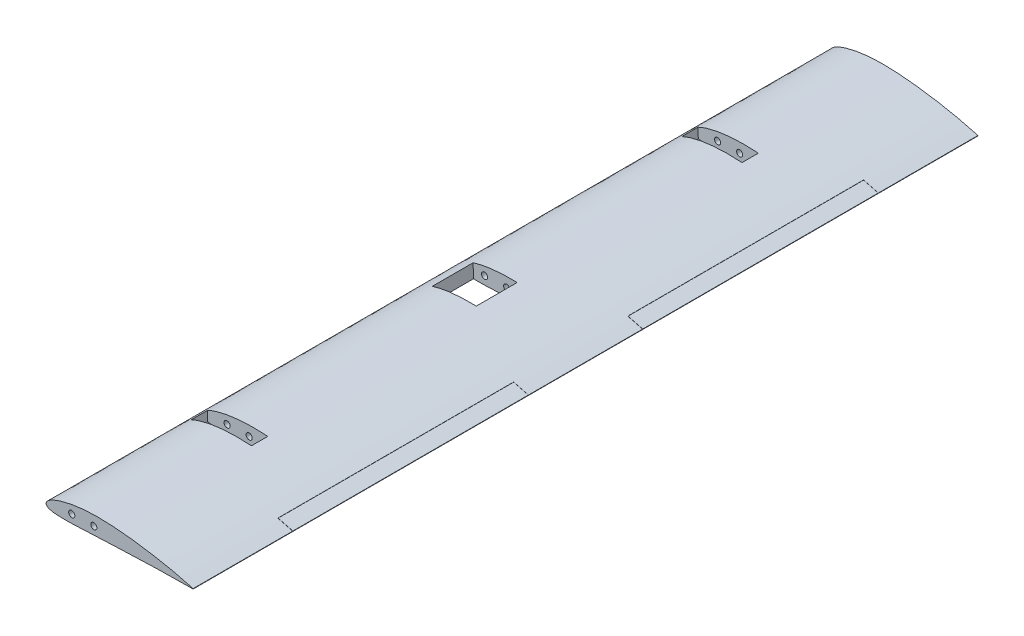
SolidWorks part; units mm, degrees
ref_plane "Front Plane" through (0, 0, 0) normal (0, 0, 1) x (1, 0, 0)
ref_plane "Top Plane" through (0, 0, 0) normal (0, 1, 0) x (1, 0, 0)
ref_plane "Right Plane" through (0, 0, 0) normal (1, 0, 0) x (0, 0, -1)
curve "NACA 4412"
  spline degree 3 poles (25.4, 0.033, 0) (24.9771, 0.1481, 0) (24.1334, 0.3778, 0) (22.4431, 0.7955, 0) (20.3293, 1.2569, 0) (17.7869, 1.7118, 0) (15.2464, 2.0846, 0) (12.7045, 2.3505, 0) (10.1628, 2.5164, 0) (8.041, 2.5181, 0) (6.3469, 2.4009, 0) (5.0745, 2.2465, 0) (3.7995, 2.0188, 0) (2.7428, 1.745, 0) (1.8961, 1.4685, 0) (1.2577, 1.2074, 0) (0.7129, 0.9251, 0) (0.2401, 0.5874, 0) (-0.1715, 0.0442, 0) (0.2727, -0.3711, 0) (0.7261, -0.5342, 0) (1.266, -0.6443, 0) (1.9036, -0.7002, 0) (2.7513, -0.7398, 0) (3.8103, -0.7368, 0) (5.0806, -0.7013, 0) (6.3499, -0.6336, 0) (8.0433, -0.5544, 0) (10.1596, -0.4528, 0) (12.7001, -0.3574, 0) (15.2397, -0.2514, 0) (17.7796, -0.1611, 0) (20.3198, -0.0947, 0) (22.4366, -0.061, 0) (24.13, -0.0388, 0) (24.9767, -0.035, 0) (25.4, -0.033, 0) knots 0 0 0 0 0.025305 0.050488 0.10052 0.150191 0.199587 0.24874 0.297716 0.346601 0.371103 0.395726 0.42057 0.445825 0.458702 0.47192 0.485786 0.493461 0.506863 0.516148 0.522766 0.535269 0.547551 0.559786 0.584229 0.608681 0.633151 0.657622 0.706558 0.755482 0.804406 0.85332 0.902221 0.951113 0.975557 1 1 1 1
sketch "Sketch2" plane through (0, 0, 0) normal (0, 0, 1) x (1, 0, 0)
  line L1 (228.6, 12.387) -> (228.6, 11.7928)
  line L2 (40.005, 31.2493) -> (40.005, 5.6305) construction
  line L4 (74.2832, 19.3375) -> (40.005, 18.4399) construction
  line L5 (0, 0) -> (0, 12.7) construction
  line L6 (40.005, 18.4399) -> (60.8151, 18.4399) construction
  circle A0 centre (40.005, 18.4399) radius 4.7625
  circle A1 centre (74.2832, 19.3375) radius 4.7625
  spline S1 degree 3 poles (228.6, 12.387) (224.795, 13.4228) (217.2034, 15.4895) (201.9951, 19.2471) (182.9766, 23.3988) (160.101, 27.4914) (137.2432, 30.846) (114.3726, 33.2389) (91.504, 34.7313) (72.413, 34.7464) (57.1699, 33.6918) (45.7222, 32.3028) (34.2497, 30.2543) (24.7428, 27.7908) (17.1245, 25.3027) (11.3801, 22.9538) (6.4787, 20.4136) (2.2242, 17.375) (-1.4793, 12.488) (2.5182, 8.7506) (6.5972, 7.2835) (11.455, 6.2932) (17.1921, 5.7898) (24.819, 5.4335) (34.3469, 5.4602) (45.7763, 5.78) (57.1976, 6.389) (72.4334, 7.1015) (91.4748, 8.016) (114.3327, 8.8746) (137.1833, 9.8281) (160.036, 10.6401) (182.8906, 11.2375) (201.9369, 11.5408) (217.1729, 11.7405) (224.791, 11.7754) (228.6, 11.7928) knots 0 0 0 0 0.025305 0.050488 0.10052 0.150191 0.199587 0.24874 0.297716 0.346601 0.371103 0.395726 0.42057 0.445825 0.458702 0.47192 0.485786 0.493461 0.506863 0.516148 0.522766 0.535269 0.547551 0.559786 0.584229 0.608681 0.633151 0.657622 0.706558 0.755482 0.804406 0.85332 0.902221 0.951113 0.975557 1 1 1 1
  point P11 (40.005, 18.4399)
  dimension "D3" = 9.525
  dimension "D4" = 9.525
  dimension "D1" = 228.6
  dimension "D5" = 34.29
  dimension "D6" = 12.7
  dimension "D8" = 1.5
  dimension "D9" = 40.005
extrude "Extrude airfoil" add sketch "Sketch2" along normal blind 1219.2
sketch "Sketch3" plane through (0, 0, 0) normal (0, 1, 0) x (1, 0, 0)
  line L1 (228.6, -520.7) -> (205.74, -520.7)
  line L4 (205.74, -520.7) -> (205.74, -154.94)
  line L5 (228.6, -154.94) -> (205.74, -154.94)
  line L8 (0, 0) -> (0, -1219.2) construction
  line L9 (0, -609.6) -> (228.6, -609.6) construction
  line L10 (228.6, -1064.26) -> (228.6, -698.5)
  line L15 (228.6, -154.94) -> (228.6, -520.7)
  line L17 (228.6, -1219.2) -> (228.6, 0) construction
  line L18 (228.6, -1064.26) -> (205.74, -1064.26)
  line L19 (205.74, -698.5) -> (205.74, -1064.26)
  line L20 (228.6, -698.5) -> (205.74, -698.5)
  dimension "D1" = 22.86
  dimension "D2" = 365.76
  dimension "D3" = 88.9
extrude "Ailerons" cut sketch "Sketch3" against normal through all and the other way through all thin
ref_plane "Plane1" through (-0.4551, 17.3804, 0) normal (-0.0262, 0.9997, 0) x (0, 0, -1)
sketch "Sketch5" plane through (-0.4551, 17.3804, 0) normal (-0.0262, 0.9997, 0) x (0, 0, -1)
  line L0 (0, 0) -> (-1219.2, 0)
  line L1 (-609.6, 0) -> (-609.6, -227.3868) construction
  line L2 (-609.6, -57.15) -> (-990.6, -57.15) construction
  line L3 (-215.9, -10.16) -> (-241.3, -104.14) construction
  line L4 (-1003.3, -104.14) -> (-977.9, -104.14)
  line L5 (-1003.3, -104.14) -> (-1003.3, -10.16)
  line L6 (-1003.3, -10.16) -> (-977.9, -10.16)
  line L7 (-977.9, -104.14) -> (-977.9, -10.16)
  line L8 (-1003.3, -104.14) -> (-977.9, -10.16) construction
  line L9 (-1003.3, -10.16) -> (-977.9, -104.14) construction
  line L10 (-215.9, -104.14) -> (-241.3, -10.16) construction
  line L11 (-241.3, -104.14) -> (-241.3, -10.16)
  line L12 (-215.9, -104.14) -> (-215.9, -10.16)
  line L13 (-215.9, -104.14) -> (-241.3, -104.14)
  line L14 (-215.9, -10.16) -> (-241.3, -10.16)
  line L16 (-577.85, -91.44) -> (-641.35, -91.44)
  line L17 (-577.85, -91.44) -> (-577.85, -22.86)
  line L18 (-577.85, -22.86) -> (-641.35, -22.86)
  line L19 (-641.35, -91.44) -> (-641.35, -22.86)
  point P19 (-609.6, -22.86)
  dimension "D1" = 1219.2
  dimension "D2" = 57.15
  dimension "D3" = 25.4
  dimension "D4" = 93.98
  dimension "D5" = 381
  dimension "D6" = 22.86
  dimension "D7" = 91.44
  dimension "D8" = 31.75
extrude "Cut-Extrude1" cut sketch "Sketch5" against normal through all and the other way through all contours L12 L14 L11 L13 | L7 L6 L5 L4 | L18 L19 L16 L17
equation "\"span\"= 48"
equation "\"D1@Extrude airfoil\"=\"span\""
equation "\"wing_chord\"= 9"
equation "\"D1@Sketch2\"= \"wing_chord\""
equation "\"D1@Sketch3\"=\"wing_chord\"*0.1"
equation "\"D2@Sketch3\"=\"span\"/2*0.6"
equation "\"fuse_len\"= 15"
equation "\"fuse_height\"= 5"
equation "\"fuse_wid\"= 5"
equation "\"foam_t\"= 0.1875"
equation "\"main_spar_len\"= 36"
equation "\"x_fuse_to_wing\"= 3"
equation "\"x_cg_from_le\"= 2.25"
equation "\"boom_len\"= 30"
equation "\"wing_spar_d\"= 0.375"
equation "\"wing_spar_spacing\"= 1.35"
equation "\"D3@Sketch2\"=\"wing_spar_d\""
equation "\"D4@Sketch2\"=\"wing_spar_d\""
equation "\"wing_angle\"= 1.5"
equation "\"boom_d\"= 0.75"
equation "\"wing_spar_l\"= 48"
equation "\"wing_mount_l\"= 2.5"
equation "\"D8@Sketch2\"=\"wing_angle\""
equation "\"D1@Sketch5\"=\"span\""
equation "\"D2@Sketch5\"=\"x_cg_from_le\""
equation "\"D3@Sketch5\"=\"boom_mount_l\""
equation "\"D5@Sketch5\"=\"boom_len\"/2"
equation "\"D5@Sketch2\"= \"wing_spar_spacing\""
equation "\"D9@Sketch2\"= \"x_cg_from_le\" - \"wing_spar_spacing\"/2"
equation "\"D6@Sketch5\"= \"x_cg_from_le\" - \"wing_spar_spacing\""
equation "\"D7@Sketch5\"= \"wing_chord\"*0.4"
equation "\"boom_mount_l\"= 1"
equation "\"vstab_span\"= 6.5"
equation "\"hstab_span\"= 15.25"
equation "\"tail_chord\"= 5"
equation "\"D8@Sketch5\"= \"wing_mount_l\"/2"
